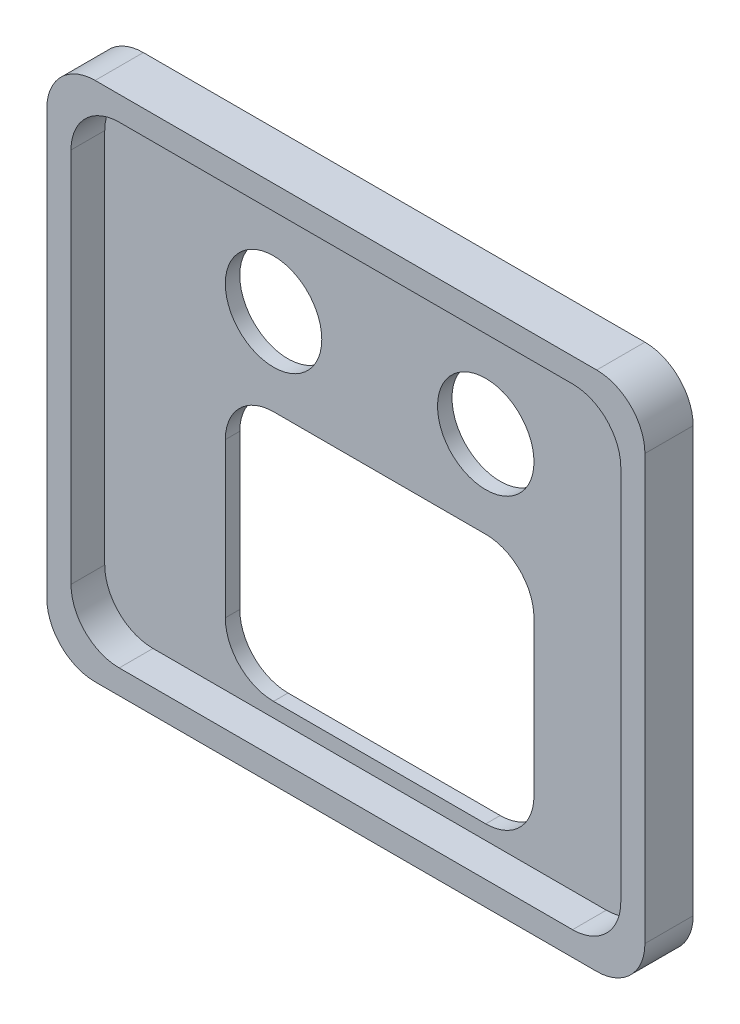
SolidWorks part; units mm, degrees
ref_plane "前视基准面" through (0, 0, 0) normal (0, 0, 1) x (1, 0, 0)
ref_plane "上视基准面" through (0, 0, 0) normal (0, 1, 0) x (1, 0, 0)
ref_plane "右视基准面" through (0, 0, 0) normal (1, 0, 0) x (0, 0, -1)
other "Configuration Table"
sketch "草图1" plane through (0, 0, 0) normal (0, 0, 1) x (1, 0, 0)
  line L1 (10, 108) -> (114, 108)
  line L2 (0, 98) -> (0, 10)
  line L3 (10, 0) -> (114, 0)
  line L4 (124, 98) -> (124, 10)
  arc A0 (0, 10) -> (10, 0) centre (10, 10) ccw
  arc A1 (124, 10) -> (114, 0) centre (114, 10) cw
  arc A2 (114, 108) -> (124, 98) centre (114, 98) cw
  arc A3 (10, 108) -> (0, 98) centre (10, 98) ccw
  dimension "D1" = 10
extrude "凸台-拉伸1" add sketch "草图1" along normal blind 10
sketch "草图2" plane through (0, 0, 10) normal (0, 0, 1) x (1, 0, 0)
  line L0 (0, 98) -> (0, 10) construction
  line L1 (15, 103) -> (109, 103)
  line L2 (5, 93) -> (5, 15)
  line L3 (15, 5) -> (109, 5)
  line L4 (119, 93) -> (119, 15)
  line L5 (124, 10) -> (124, 98) construction
  line L6 (114, 108) -> (10, 108) construction
  line L7 (10, 0) -> (114, 0) construction
  arc A0 (5, 15) -> (15, 5) centre (15, 15) ccw
  arc A1 (109, 5) -> (119, 15) centre (109, 15) ccw
  arc A2 (119, 93) -> (109, 103) centre (109, 93) ccw
  arc A3 (15, 103) -> (5, 93) centre (15, 93) ccw
  dimension "D5" = 10
  dimension "D1" = 5
  dimension "D2" = 5
  dimension "D3" = 5
  dimension "D4" = 5
extrude "切除-拉伸1" cut sketch "草图2" against normal blind 7
sketch "草图3" plane through (0, 0, 0) normal (0, 0, -1) x (-1, 0, 0)
  line L0 (-124, 10) -> (-124, 98) construction
  line L1 (-84, 60) -> (-40, 60)
  line L2 (-94, 50) -> (-94, 18)
  line L3 (-84, 8) -> (-40, 8)
  line L4 (-30, 50) -> (-30, 18)
  line L5 (0, 98) -> (0, 10) construction
  line L6 (-10, 0) -> (-114, 0) construction
  arc A0 (-84, 8) -> (-94, 18) centre (-84, 18) cw
  arc A1 (-30, 18) -> (-40, 8) centre (-40, 18) cw
  arc A2 (-30, 50) -> (-40, 60) centre (-40, 50) ccw
  arc A3 (-84, 60) -> (-94, 50) centre (-84, 50) ccw
  dimension "D5" = 10
  dimension "D1" = 30
  dimension "D2" = 30
  dimension "D3" = 8
  dimension "D4" = 60
extrude "切除-拉伸2" cut sketch "草图3" against normal blind 7
sketch "草图4" plane through (0, 0, 0) normal (0, 0, -1) x (-1, 0, 0)
  line L0 (-124, 10) -> (-124, 98) construction
  line L1 (0, 98) -> (0, 10) construction
  line L2 (-114, 108) -> (-10, 108) construction
  circle A0 centre (-84, 78) radius 10
  circle A1 centre (-40, 78) radius 10
  dimension "D5" = 20
  dimension "D6" = 20
  dimension "D1" = 40
  dimension "D2" = 40
  dimension "D3" = 30
  dimension "D4" = 30
extrude "切除-拉伸3" cut sketch "草图4" against normal blind 7
